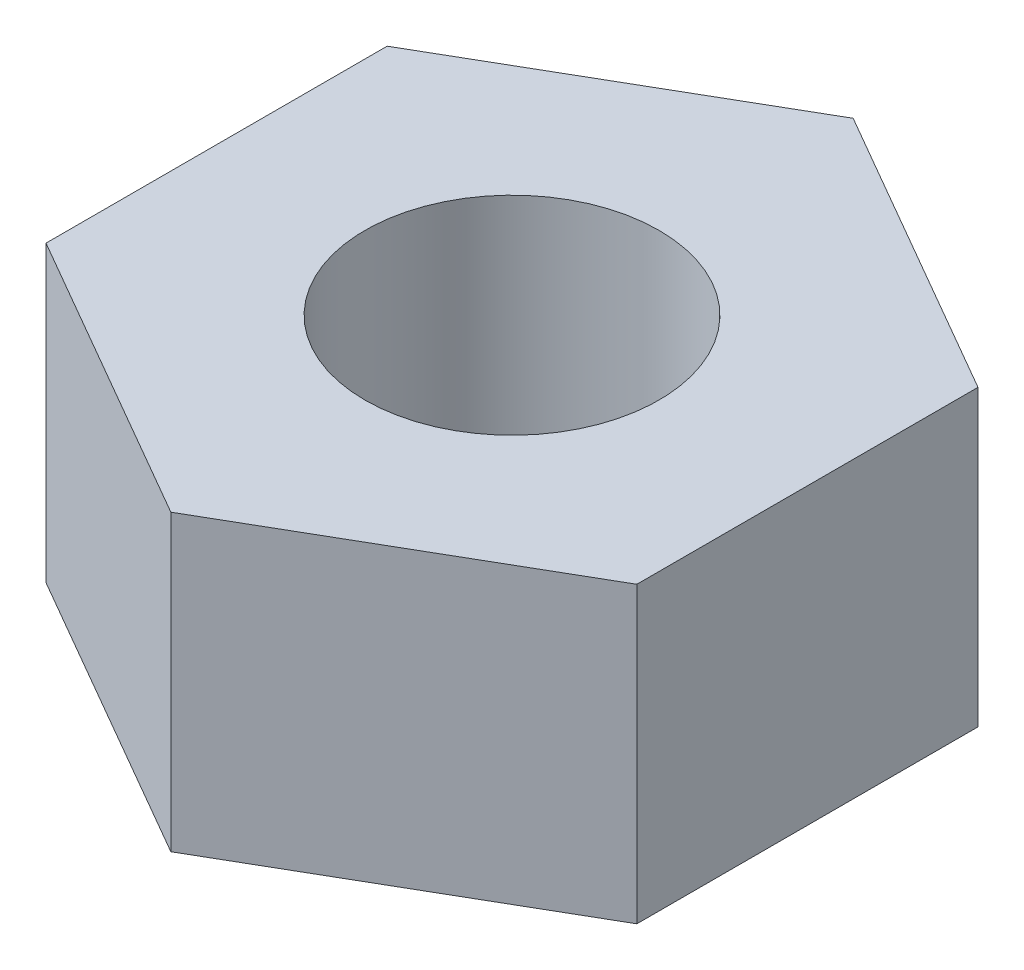
SolidWorks part; units mm, degrees
ref_plane "Front Plane" through (0, 0, 0) normal (0, 0, 1) x (1, 0, 0)
ref_plane "Top Plane" through (0, 0, 0) normal (0, 1, 0) x (1, 0, 0)
ref_plane "Right Plane" through (0, 0, 0) normal (1, 0, 0) x (0, 0, -1)
sketch "Sketch1" plane through (0, 0, 0) normal (0, 1, 0) x (1, 0, 0)
  line L1 (0, -7.366) -> (6.3791, -3.683)
  line L2 (6.3791, -3.683) -> (6.3791, 3.683)
  line L3 (6.3791, 3.683) -> (0, 7.366)
  line L4 (0, 7.366) -> (-6.3791, 3.683)
  line L5 (-6.3791, 3.683) -> (-6.3791, -3.683)
  line L6 (-6.3791, -3.683) -> (0, -7.366)
  circle A0 centre (0, 0) radius 6.3791 construction
  circle A1 centre (0, 0) radius 3.175
  dimension "D2" = 6.35
  dimension "D1" = 7.366
extrude "Boss-Extrude1" add sketch "Sketch1" along normal blind 6.35
